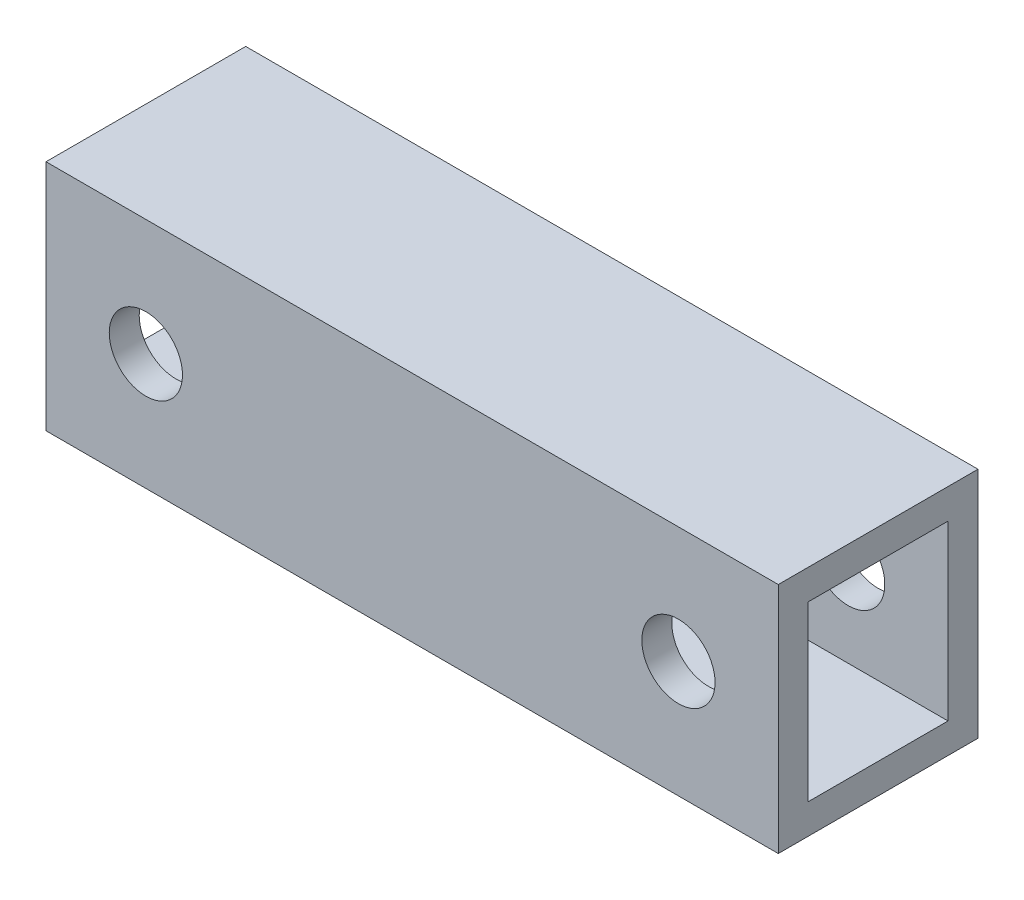
SolidWorks part; units mm, degrees
ref_plane "Front Plane" through (0, 0, 0) normal (0, 0, 1) x (1, 0, 0)
ref_plane "Top Plane" through (0, 0, 0) normal (0, 1, 0) x (1, 0, 0)
ref_plane "Right Plane" through (0, 0, 0) normal (1, 0, 0) x (0, 0, -1)
sketch "Soft_contact_and_wrap_profile" plane through (0, 0, 0) normal (0, 0, 1) x (1, 0, 0)
  line L1 (54, -17) -> (76, -17)
  line L2 (54, -17) -> (54, -10)
  line L3 (54, -10) -> (76, -10)
  line L4 (76, -17) -> (76, -10)
  dimension "D1" = 22
  dimension "D2" = 7
extrude "Soft_contact_and_wrap" add sketch "Soft_contact_and_wrap_profile" along normal blind 6 from offset 1
sketch "Fixed_bar_slip_pocket_profile" plane through (0, 0, 0) normal (0, 0, 1) x (1, 0, 0)
  line L1 (53, -16.1) -> (77, -16.1)
  line L2 (53, -16.1) -> (53, -10.9)
  line L3 (53, -10.9) -> (77, -10.9)
  line L4 (77, -16.1) -> (77, -10.9)
  dimension "D1" = 24
  dimension "D2" = 5.2
extrude "Slip_pocket" cut sketch "Fixed_bar_slip_pocket_profile" along normal blind 4.2 from offset 0.1
sketch "Pad_capture_M2_profile" plane through (0, 0, 0) normal (0, 0, 1) x (1, 0, 0)
  circle A0 centre (57, -13.5) radius 1.1
  circle A1 centre (73, -13.5) radius 1.1
  dimension "D1" = 2.2
  dimension "D2" = 2.2
extrude "Pad_capture_M2" cut sketch "Pad_capture_M2_profile" along normal through all from offset 50
